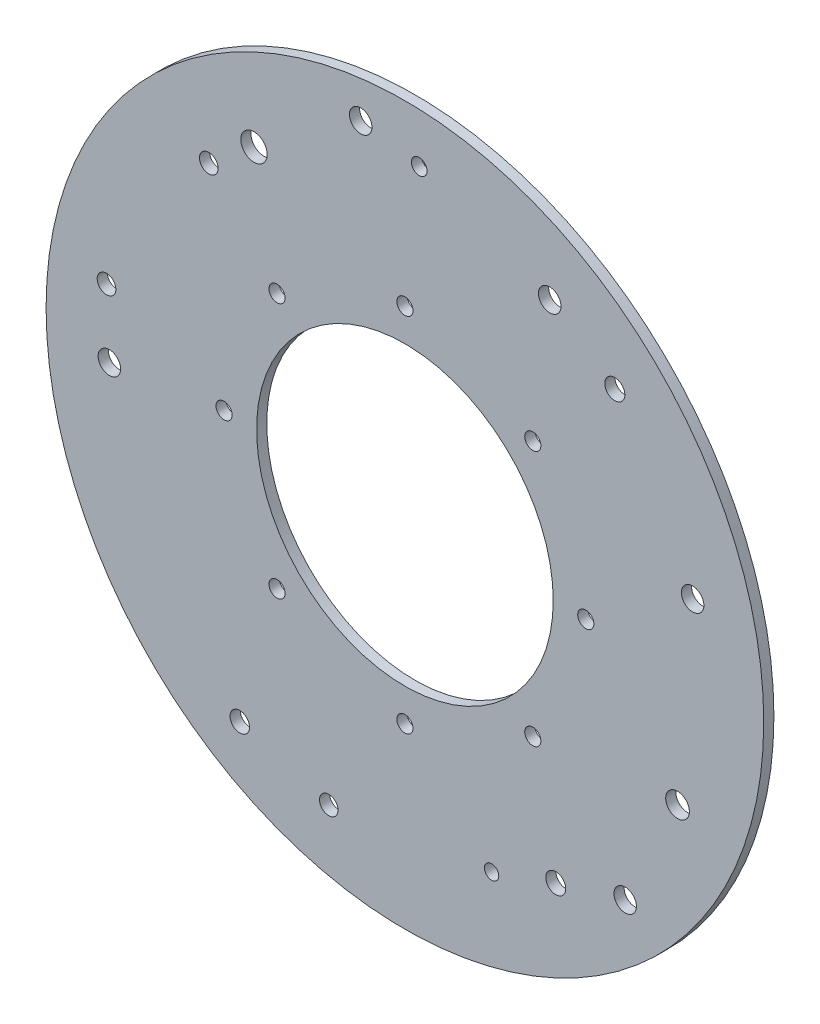
SolidWorks part; units mm, degrees
ref_plane "Front Plane" through (0, 0, 0) normal (0, 0, 1) x (1, 0, 0)
ref_plane "Top Plane" through (0, 0, 0) normal (0, 1, 0) x (1, 0, 0)
ref_plane "Right Plane" through (0, 0, 0) normal (1, 0, 0) x (0, 0, -1)
sketch "Sketch1" plane through (0, 0, 0) normal (0, 0, 1) x (1, 0, 0)
  circle A0 centre (0, 0) radius 211.6704
  circle A1 centre (160.8023, -67.724) radius 6.985
  circle A2 centre (129.9312, -131.7473) radius 6.6294
  circle A3 centre (88.9838, -143.6091) radius 5.8928
  circle A4 centre (51.1327, -156.8171) radius 4.2291
  circle A5 centre (-44.9301, -170.6143) radius 5.461
  circle A6 centre (-97.4039, -154.3431) radius 5.7531
  circle A7 centre (-174.3304, -9.3269) radius 6.6294
  circle A8 centre (-176.0119, 29.9568) radius 5.4991
  circle A9 centre (-89.0372, 143.4338) radius 7.7978
  circle A10 centre (-26.096, 188.2775) radius 6.6421
  circle A11 centre (8.4277, 182.1967) radius 4.6228
  circle A12 centre (85.4227, 152.5803) radius 6.6421
  circle A13 centre (123.8123, 126.1847) radius 5.9182
  circle A14 centre (169.7101, 41.9354) radius 6.6421
  circle A15 centre (-115.6919, 121.8667) radius 5.4991
  point P32 (0, 0)
  point P33 (0, 0)
  point P34 (-89.0372, 143.4338)
  dimension "D1" = 188.2775
  dimension "D2" = 182.1967
  dimension "D3" = 152.5803
  dimension "D4" = 126.1847
  dimension "D5" = 41.9354
  dimension "D6" = 67.724
  dimension "D7" = 131.7473
  dimension "D8" = 143.6091
  dimension "D9" = 156.8171
  dimension "D10" = 170.6143
  dimension "D11" = 154.3431
  dimension "D12" = 9.3269
  dimension "D13" = 29.9568
  dimension "D14" = 121.8667
  dimension "D15" = 143.4338
  dimension "D16" = 176.0119
  dimension "D17" = 115.6919
  dimension "D18" = 89.0372
  dimension "D19" = 26.096
  dimension "D20" = 8.4277
  dimension "D21" = 85.4227
  dimension "D22" = 123.8123
  dimension "D23" = 169.7101
  dimension "D24" = 160.8023
  dimension "D25" = 129.9312
  dimension "D26" = 88.9838
  dimension "D27" = 51.1327
  dimension "D28" = 44.9301
  dimension "D29" = 97.4039
  dimension "D30" = 174.3304
extrude "Boss-Extrude1" add sketch "Sketch1" along normal blind 6
sketch "Sketch2" plane through (0, 0, 6) normal (0, 0, 1) x (1, 0, 0)
  circle A0 centre (0, 0) radius 87.5
  dimension "D1" = 175
extrude "Cut-Extrude1" cut sketch "Sketch2" against normal through all
sketch "Sketch3" plane through (0, 0, 6) normal (0, 0, 1) x (1, 0, 0)
  line L0 (0, 0) -> (0, 106.68) construction
  line L1 (0, 0) -> (106.68, 0) construction
  line L2 (0, 0) -> (75.4342, 75.4342) construction
  circle A0 centre (0, 0) radius 106.68 construction
  dimension "D1" = 213.36
  dimension "D2" = 45
hole_wizard "3/8 (0.375) Diameter Hole1" positions "3DSketch2" profile "Sketch5" hole size "3/8" standard "ANSI Inch" end condition through all
sketch3d "3DSketch2"
  point P0 (0, 106.68, 6)
  point P3 (75.4342, 75.4342, 6)
  point P7 (0, 106.68, 6)
  point P9 (75.4342, 75.4342, 6)
sketch "Sketch5" plane through (0, 106.68, 6) normal (1, 0, 0) x (0, -1, 0)
  line L0 (0, 0) -> (0, 6)
  line L1 (0, 6) -> (4.7625, 6)
  line L2 (4.7625, 6) -> (4.7625, 0)
  line L5 (4.7625, 0) -> (0, 0)
  line L11 (0, -6.35) -> (0, 107.95) construction
  dimension "Thru Hole Dia." = 9.525
  dimension "Thru Hole Depth" = 6
pattern_circular "CirPattern1" count 4 over 360 about axis through (0, 0, 0) along (0, 0, 1) of "3/8 (0.375) Diameter Hole1"
sketch "Sketch6" plane through (0, 0, 6) normal (0, 0, 1) x (1, 0, 0)
  line L0 (-40.879, 152.7388) -> (33.4464, 152.7388) construction
  text T0 "top/outer" font "Century Gothic" height in points 30
